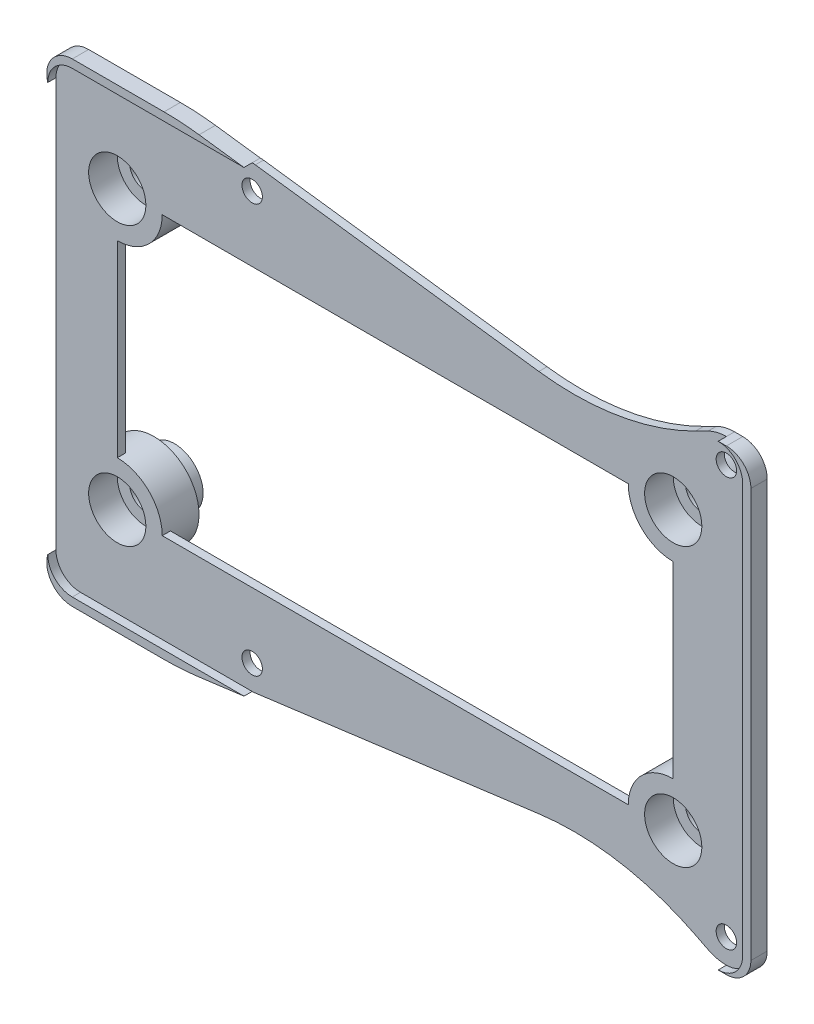
SolidWorks part; units mm, degrees
ref_plane "Ebene vorne" through (0, 0, 0) normal (0, 0, 1) x (1, 0, 0)
ref_plane "Ebene oben" through (0, 0, 0) normal (0, 1, 0) x (1, 0, 0)
ref_plane "Ebene rechts" through (0, 0, 0) normal (1, 0, 0) x (0, 0, -1)
sketch "Skizze1" plane through (0, 0, 0) normal (0, 0, 1) x (1, 0, 0)
  line L0 (0, 34) -> (0, 36.5)
  circle A0 centre (0, 34) radius 3.5
  circle A1 centre (68, 34) radius 3.5
  circle A2 centre (68, 0) radius 3.5
  circle A3 centre (0, 0) radius 3.5
  circle A4 centre (0, 34) radius 2
  circle A5 centre (68, 34) radius 2
  circle A6 centre (68, 0) radius 2
  circle A7 centre (0, 0) radius 2
  point P14 (0, 0)
  point P15 (0, 0)
  dimension "D3" = 7
  dimension "D5" = 4
  dimension "D1" = 68
  dimension "D2" = 34
  dimension "D4" = 2.5
extrude "Aufsatz-Linear austragen1" add sketch "Skizze1" along normal blind 2.5 contours A0 | A3 | A1 | A2 | A7 | A5 | A4 | A6
sketch "Skizze2" plane through (0, 0, 2.5) normal (0, 0, 1) x (1, 0, 0)
  circle A1 centre (0, 34) radius 2
  circle A2 centre (68, 34) radius 2
  circle A4 centre (0, 0) radius 2
  circle A5 centre (68, 0) radius 2
  circle A6 centre (0, 34) radius 5.5
  circle A7 centre (68, 34) radius 5.5
  circle A8 centre (68, 0) radius 5.5
  circle A9 centre (0, 0) radius 5.5
  dimension "D1" = 4
  dimension "D5" = 11
extrude "Aufsatz-Linear austragen3" add sketch "Skizze2" along normal blind 1
sketch "Skizze3" plane through (0, 0, 3.5) normal (0, 0, 1) x (1, 0, 0)
  circle A1 centre (0, 34) radius 3.5
  circle A2 centre (68, 34) radius 3.5
  circle A4 centre (0, 0) radius 3.5
  circle A5 centre (68, 0) radius 3.5
  circle A6 centre (0, 34) radius 5.5
  circle A7 centre (68, 34) radius 5.5
  circle A8 centre (68, 0) radius 5.5
  circle A9 centre (0, 0) radius 5.5
  circle A10 centre (68, 0) radius 5.5 construction
  circle A11 centre (68, 34) radius 5.5 construction
  circle A12 centre (0, 34) radius 5.5 construction
  circle A13 centre (0, 0) radius 5.5 construction
  point P12 (0, 0)
  point P13 (-15.9869, 6)
  point P14 (0, 0)
  dimension "D1" = 7
extrude "Aufsatz-Linear austragen4" add sketch "Skizze3" along normal blind 2.5
sketch "Skizze4" plane through (0, 0, 6) normal (0, 0, 1) x (1, 0, 0)
  line L0 (0, 17) -> (68, 17) construction
  line L1 (5.5, 0) -> (62.5, 0)
  line L6 (0, 34) -> (0, 0) construction
  line L7 (68, 34) -> (68, 0) construction
  line L8 (5.5, 34) -> (62.5, 34)
  line L9 (-4.5, 45) -> (74.5, 45)
  line L10 (-7.5, 42) -> (-7.5, -8)
  line L11 (-4.5, -11) -> (74.5, -11)
  line L12 (77.5, 42) -> (77.5, -8)
  line L13 (0, 28.5) -> (0, 5.5)
  line L14 (68, 5.5) -> (68, 28.5)
  arc A0 (0, 28.5) -> (5.5, 34) centre (0, 34) ccw
  circle A1 centre (0, 34) radius 3.5
  circle A2 centre (68, 34) radius 3.5
  circle A3 centre (68, 0) radius 3.5
  arc A4 (74.5, 45) -> (77.5, 42) centre (74.5, 42) cw
  arc A5 (74.5, -11) -> (77.5, -8) centre (74.5, -8) ccw
  arc A6 (-7.5, -8) -> (-4.5, -11) centre (-4.5, -8) ccw
  arc A7 (-4.5, 45) -> (-7.5, 42) centre (-4.5, 42) ccw
  circle A8 centre (74.5, 42) radius 1.25
  circle A9 centre (74.5, -8) radius 1.25
  circle A10 centre (16.5, 42) radius 1.25
  circle A11 centre (16.5, -8) radius 1.25
  circle A12 centre (0, 0) radius 3.5
  arc A14 (0, 5.5) -> (5.5, 0) centre (0, 0) cw
  arc A15 (62.5, 34) -> (68, 28.5) centre (68, 34) ccw
  arc A16 (62.5, 0) -> (68, 5.5) centre (68, 0) cw
  circle A17 centre (68, 0) radius 3.5 construction
  circle A18 centre (0, 34) radius 5.5 construction
  circle A19 centre (68, 34) radius 5.5 construction
  circle A20 centre (68, 0) radius 5.5 construction
  point P24 (68, 28)
  point P31 (77.5, 45)
  point P36 (-7.5, -11)
  point P39 (-7.5, 45)
  point P51 (60.3986, 0)
  circle M9 centre (0, 34) radius 5.5
  dimension "D3" = 3
  dimension "D4" = 2.5
  dimension "D5" = 2.5
  dimension "D6" = 2.5
  dimension "D1" = 85
  dimension "D2" = 56
  dimension "D7" = 58
  dimension "D8" = 9.5
extrude "Aufsatz-Linear austragen7" add sketch "Skizze4" along normal blind 1 contours L9 A7 L10 A6 L11 A5 L12 A4 A12 L13 L8 A2 L14 A3 L1 A11 A10 A9 A8 M9 | A1
sketch "Skizze6" plane through (0, 0, 7) normal (0, 0, 1) x (1, 0, 0)
  line L0 (-4.5, 45) -> (74.5, 45) construction
  line L1 (16.8899, 44.9746) -> (51.5651, 40.4292)
  line L2 (70.7234, 43.6891) -> (72.2678, 44.4686)
  line L3 (16.5, 45) -> (16.5, 49.6634)
  line L4 (16.5, 49.6634) -> (74.5, 49.6634)
  line L6 (-7.5, 17) -> (77.5, 17) construction
  line L7 (-7.5, 42) -> (-7.5, -8) construction
  line L8 (77.5, 42) -> (77.5, -8) construction
  line L14 (74.5, 45) -> (74.5, 49.6634)
  line L15 (74.5, -11) -> (74.5, -15.6634)
  line L16 (16.5, -15.6634) -> (74.5, -15.6634)
  line L17 (16.5, -11) -> (16.5, -15.6634)
  line L18 (70.7234, -9.6891) -> (72.2678, -10.4686)
  line L19 (16.8899, -10.9746) -> (51.5651, -6.4292)
  arc A0 (16.8899, 44.9746) -> (16.5, 45) centre (16.5, 42) ccw
  arc A1 (51.5651, 40.4292) -> (70.7234, 43.6891) centre (55.8541, 73.1493) ccw
  arc A4 (72.2678, 44.4686) -> (74.5, 45) centre (74.5, 40.046) cw
  arc A5 (77.5, 42) -> (74.5, 45) centre (74.5, 42) ccw construction
  arc A6 (72.2678, -10.4686) -> (74.5, -11) centre (74.5, -6.046) ccw
  arc A7 (51.5651, -6.4292) -> (70.7234, -9.6891) centre (55.8541, -39.1493) cw
  arc A8 (16.8899, -10.9746) -> (16.5, -11) centre (16.5, -8) cw
  dimension "D1" = 33
extrude "Schnitt-Linear austragen1" cut sketch "Skizze6" against normal up to surface (1 mm away) up to face at (17.75, -8, 6)
sketch "Skizze7" plane through (0, 0, 6) normal (0, 0, -1) x (-1, 0, 0)
  line L1 (0, 17) -> (-103.3819, 17) construction
  line L2 (0, 28.5) -> (0, 5.5) construction
  line L4 (-77.5, 42) -> (-77.5, -8)
  line L5 (-77.5, 42) -> (-77.5, -8) construction
  line L9 (-74.5, 45) -> (-75.5, 45)
  line L11 (-78.5, 42) -> (-78.5, -8)
  line L12 (-74.5, -11) -> (-75.5, -11)
  line L13 (4.5, -11) -> (-16.5, -11)
  line L14 (-16.5, -11) -> (-11.0066, -11.7201)
  line L15 (-6.7176, -12) -> (4.5, -12)
  line L16 (-6.7176, 46) -> (4.5, 46)
  line L17 (-16.5, 45) -> (-11.0066, 45.7201)
  line L18 (-51.5651, -6.4292) -> (-16.8899, -10.9746) construction
  line L19 (4.5, 45) -> (-16.5, 45)
  arc A0 (-74.5, 45) -> (-77.5, 42) centre (-74.5, 42) ccw
  arc A4 (-75.5, 45) -> (-78.5, 42) centre (-75.5, 42) ccw
  arc A5 (-75.5, -11) -> (-78.5, -8) centre (-75.5, -8) cw
  arc A6 (-74.5, -11) -> (-77.5, -8) centre (-74.5, -8) cw
  arc A7 (-11.0066, -11.7201) -> (-6.7176, -12) centre (-6.7176, 21) ccw
  arc A8 (4.5, -12) -> (7.5, -8) centre (4.5, -8.875) ccw
  arc A10 (4.5, -11) -> (7.5, -8) centre (4.5, -8) ccw
  arc A11 (4.5, -11) -> (7.5, -8) centre (4.5, -8) ccw construction
  arc A12 (4.5, 45) -> (7.5, 42) centre (4.5, 42) cw
  arc A13 (4.5, 46) -> (7.5, 42) centre (4.5, 42.875) cw
  arc A14 (-11.0066, 45.7201) -> (-6.7176, 46) centre (-6.7176, 13) cw
  point P3 (-77.5, 17)
  point P13 (-78.5, 17)
  point P19 (-77.5, 17)
  point P24 (-78.5, 17)
  dimension "D1" = 3
  dimension "D3" = 33
  dimension "D2" = 1
  dimension "D4" = 1
extrude "Aufsatz-Linear austragen8" add sketch "Skizze7" against normal blind 2
